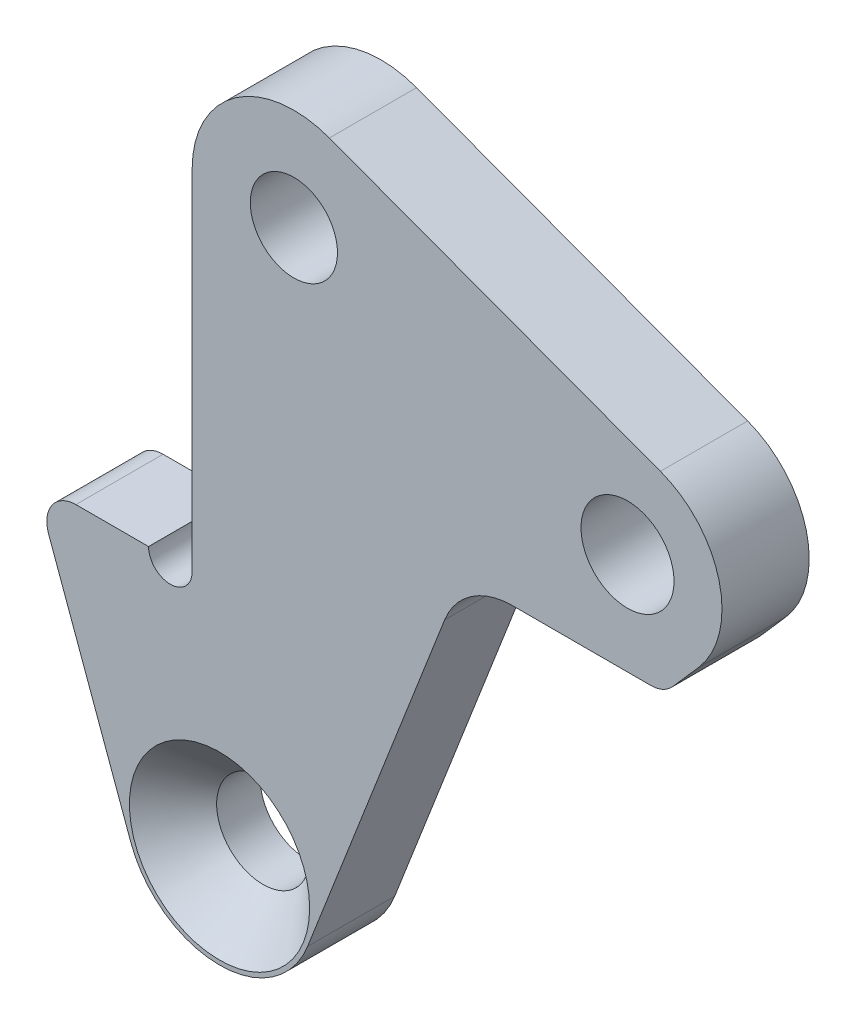
SolidWorks part; units mm, degrees
ref_plane "前视基准面" through (0, 0, 0) normal (0, 0, 1) x (1, 0, 0)
ref_plane "上视基准面" through (0, 0, 0) normal (0, 1, 0) x (1, 0, 0)
ref_plane "右视基准面" through (0, 0, 0) normal (1, 0, 0) x (0, 0, -1)
sketch "草图1" plane through (0, 0, 0) normal (0, 0, 1) x (1, 0, 0)
  line L0 (-7.5, -12) -> (-3.5, -12)
  line L1 (-3.5, -12) -> (-3.5, 0)
  line L2 (-8.4397, -13.342) -> (-5.6118, -21.1116)
  line L3 (1.2196, 3.2806) -> (12.6097, -0.9537)
  line L4 (-0.1146, -22.1432) -> (13.9204, -6.1432)
  line L5 (-8.4373, -12.6515) -> (-3.2806, 1.2196) construction
  circle A0 centre (0, 0) radius 1.5
  arc A1 (-5.6118, -21.1116) -> (-0.1146, -22.1432) centre (-2.5578, -20) ccw
  circle A2 centre (-2.5578, -20) radius 1.6
  arc A3 (-7.5, -12) -> (-8.4397, -13.342) centre (-7.5, -13) ccw
  arc A4 (-3.5, 0) -> (1.2196, 3.2806) centre (0, 0) cw
  circle A5 centre (11.4772, -4) radius 1.6
  arc A6 (13.9204, -6.1432) -> (12.6097, -0.9537) centre (11.4772, -4) ccw
  point P18 (-8.9281, -12)
  dimension "D2" = 3
  dimension "D4" = 3.2
  dimension "D5" = 3.25
  dimension "D7" = 1
  dimension "D10" = 3.25
  dimension "D11" = 3.2
  dimension "D3" = 70
  dimension "D6" = 8
  dimension "D1" = 4
  dimension "D8" = 20
  dimension "D9" = 3.5
  dimension "D13" = 4
extrude "凸台-拉伸1" add sketch "草图1" along normal mid plane 3
chamfer "倒角1" distance 1.5 angle 45 1 edges at (-0.9578, -20, 1.5)
sketch "草图2" plane through (0, 0, 1.5) normal (0, 0, 1) x (1, 0, 0)
  line L0 (-3.5, -12) -> (-7.5, -12) construction
  circle A0 centre (-4.25, -12) radius 0.75
  dimension "D1" = 1.5
extrude "切除-拉伸1" cut sketch "草图2" against normal through all
sketch "草图3" plane through (0, 0, 1.5) normal (0, 0, 1) x (1, 0, 0)
  line L0 (5.8074, -7.5) -> (12.7302, -7.5)
  line L1 (-0.1146, -22.1432) -> (13.9204, -6.1432) construction
  line L2 (12.7302, -7.5) -> (-0.1146, -22.1432)
  line L3 (0.4699, -21.1812) -> (5.8074, -7.5)
  line L4 (11.4772, -10) -> (11.4772, -4) construction
  line L5 (12.6097, -0.9537) -> (1.2196, 3.2806) construction
  circle A0 centre (11.4772, -4) radius 1.6 construction
  circle A1 centre (0, 0) radius 15.2225 construction
  circle A2 centre (11.4772, -10) radius 2.5 construction
  circle A3 centre (7.2733, -13.3725) radius 2.5 construction
  arc A4 (-5.6118, -21.1116) -> (-0.1146, -22.1432) centre (-2.5578, -20) ccw construction
  arc A5 (-0.1146, -22.1432) -> (0.4699, -21.1812) centre (-2.5578, -20) ccw
  dimension "D2" = 5
  dimension "D4" = 20.393
  dimension "D5" = 3.5
  dimension "D1" = 6
  dimension "D3" = 20.393
extrude "切除-拉伸2" cut sketch "草图3" against normal through all
fillet "圆角1" radius 2.5 1 edges at (5.8074, -7.5, 0)
fillet "圆角2" radius 1 1 edges at (12.7302, -7.5, 0)
equation "\"D1@草图1\"=5-\"D7@草图1\""
equation "\"D3@草图3\"=\"D4@草图3\""
